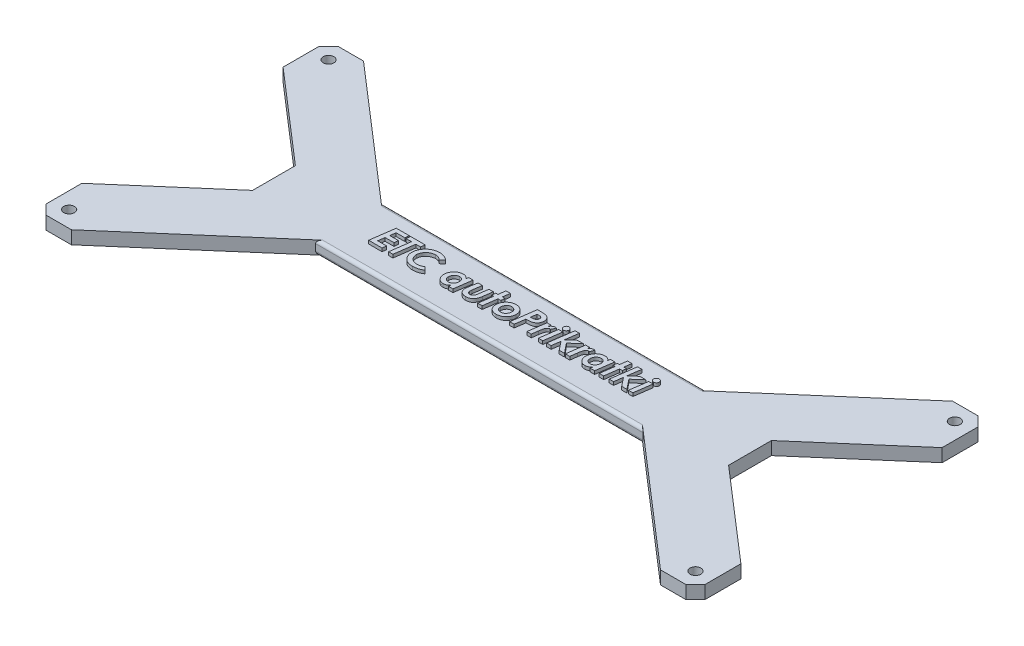
SolidWorks part; units mm, degrees
ref_plane "Front Plane" through (0, 0, 0) normal (0, 0, 1) x (1, 0, 0)
ref_plane "Top Plane" through (0, 0, 0) normal (0, 1, 0) x (1, 0, 0)
ref_plane "Right Plane" through (0, 0, 0) normal (1, 0, 0) x (0, 0, -1)
sketch "Sketch1" plane through (0, 0, 0) normal (0, 1, 0) x (1, 0, 0)
  line L0 (-100.7029, -41.7125) -> (-100.7029, -30.7434)
  line L1 (-41.7125, 100.7029) -> (-100.7029, 41.7125) construction
  line L2 (-100.7029, 41.7125) -> (-100.7029, -41.7125) construction
  line L3 (-100.7029, -41.7125) -> (-41.7125, -100.7029) construction
  line L4 (-41.7125, -100.7029) -> (41.7125, -100.7029) construction
  line L5 (41.7125, -100.7029) -> (100.7029, -41.7125) construction
  line L6 (100.7029, -41.7125) -> (100.7029, 41.7125) construction
  line L7 (100.7029, 41.7125) -> (41.7125, 100.7029) construction
  line L8 (41.7125, 100.7029) -> (-41.7125, 100.7029) construction
  line L9 (-100.7029, -30.7434) -> (-72.7473, -6.5448)
  line L10 (-72.7473, 6.5448) -> (-100.7029, 30.7434)
  line L11 (-100.7029, 30.7434) -> (-100.7029, 41.7125)
  line L12 (-100.7029, 41.7125) -> (-97.7739, 44.6414)
  line L13 (-97.7739, 44.6414) -> (-90.0196, 44.6414)
  line L14 (-90.0196, 44.6414) -> (-50, 10)
  line L15 (-50, 10) -> (50, 10)
  line L16 (0, 10) -> (0, -10)
  line L17 (50, -10) -> (-50, -10)
  line L18 (-50, -10) -> (-90.0196, -44.6414)
  line L19 (-90.0196, -44.6414) -> (-97.7739, -44.6414)
  line L20 (-97.7739, -44.6414) -> (-100.7029, -41.7125)
  line L21 (-72.7473, -6.5448) -> (-72.7473, 6.5448)
  line L22 (100.7029, -41.7125) -> (100.7029, -30.7434)
  line L23 (97.7739, -44.6414) -> (100.7029, -41.7125)
  line L24 (90.0196, -44.6414) -> (97.7739, -44.6414)
  line L25 (50, -10) -> (90.0196, -44.6414)
  line L26 (90.0196, 44.6414) -> (50, 10)
  line L27 (97.7739, 44.6414) -> (90.0196, 44.6414)
  line L28 (100.7029, 41.7125) -> (97.7739, 44.6414)
  line L29 (100.7029, 30.7434) -> (100.7029, 41.7125)
  line L30 (72.7473, 6.5448) -> (100.7029, 30.7434)
  line L31 (72.7473, -6.5448) -> (72.7473, 6.5448)
  line L32 (100.7029, -30.7434) -> (72.7473, -6.5448)
  circle A0 centre (0, 0) radius 100.7029 construction
  circle A1 centre (0, 0) radius 109 construction
  circle A2 centre (-95.7029, 39.6414) radius 1.65
  circle A3 centre (-95.7029, -39.6414) radius 1.65
  circle A4 centre (95.7029, -39.6414) radius 1.65
  circle A5 centre (95.7029, 39.6414) radius 1.65
  point P29 (-65.1865, 0)
  point P31 (-65.1865, 0)
  dimension "D1" = 218
  dimension "D2" = 3.3
  dimension "D3" = 3.3
  dimension "D4" = 5
  dimension "D5" = 5
  dimension "D6" = 5
  dimension "D7" = 5
  dimension "D8" = 20
  dimension "D9" = 10
  dimension "D10" = 7.5
  dimension "D11" = 7.5
  dimension "D12" = 10
  dimension "D13" = 5
  dimension "D14" = 5
  dimension "D15" = 50
extrude "Boss-Extrude1" add sketch "Sketch1" along normal blind 4 contours L22 L32 L31 L30 L29 L28 L27 L26 L15 L16 L17 L25 L24 L23 A4 A5 | L21 L9 L0 L20 L19 L18 L17 L16 L15 L14 L13 L12 L11 L10 A3 A2
sketch "Sketch2" plane through (0, 4, 0) normal (0, 1, 0) x (1, 0, 0)
  text T0 "<i>ETC autoPrikratki</i>" font "Century Gothic" height in points 28
  dimension "D1" = 41
  dimension "D2" = 3
extrude "Boss-Extrude2" add sketch "Sketch2" along normal blind 1
fillet "Fillet1" radius 1 4 edges at (0, 4, -10) (0, 0, -10) (0, 0, 10) (0, 4, 10)
